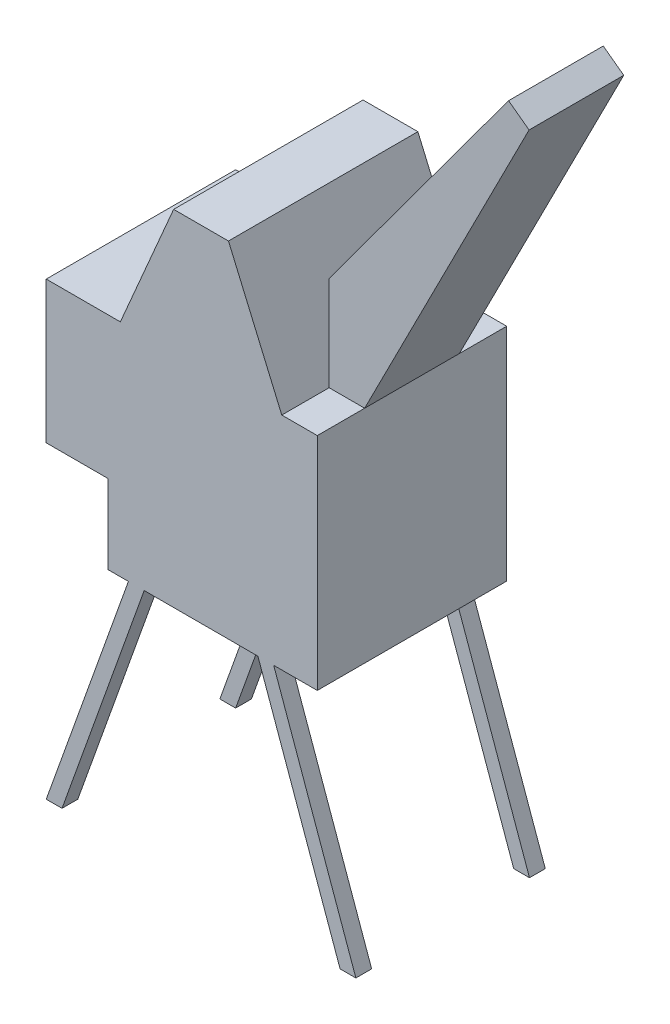
SolidWorks part; units mm, degrees
ref_plane "Front Plane" through (0, 0, 0) normal (0, 0, 1) x (1, 0, 0)
ref_plane "Top Plane" through (0, 0, 0) normal (0, 1, 0) x (1, 0, 0)
ref_plane "Right Plane" through (0, 0, 0) normal (1, 0, 0) x (0, 0, -1)
sketch "Sketch1" plane through (0, 0, 0) normal (0, 0, 1) x (1, 0, 0)
  line L0 (0, 0) -> (529.0109, 1478.7244)
  line L1 (529.0109, 1478.7244) -> (1993.215, 0)
  line L2 (1993.215, 0) -> (1464.2041, 1478.7244)
  line L3 (397.1811, 1478.7244) -> (1596.0339, 1478.7244)
  line L4 (1596.0339, 1478.7244) -> (1596.0339, 1986.7569)
  line L5 (1596.0339, 1986.7569) -> (397.1811, 1986.7569)
  line L6 (397.1811, 1986.7569) -> (397.1811, 1478.7244)
  line L7 (397.1811, 1986.7569) -> (0, 1986.7569)
  line L8 (0, 1986.7569) -> (0, 2899.7327)
  line L9 (0, 2899.7327) -> (1744.8315, 2899.7327)
  line L10 (1744.8315, 2899.7327) -> (1744.8315, 1986.7569)
  line L11 (1744.8315, 1986.7569) -> (1596.0339, 1986.7569)
  line L12 (727.2667, 2899.7327) -> (727.2667, 1986.7569)
  line L13 (1464.2041, 1478.7244) -> (0, 0)
  line L14 (1516.2315, 2899.7327) -> (1516.2315, 3509.3327)
  line L15 (1516.2315, 3509.3327) -> (2671.2271, 5077.4555)
  line L16 (2671.2271, 5077.4555) -> (2803.2371, 4980.224)
  line L17 (2803.2371, 4980.224) -> (1744.8315, 2899.7327)
  line L18 (476.9834, 2899.7327) -> (820.1619, 3698.5201)
  line L19 (820.1619, 3698.5201) -> (1173.0531, 3698.5201)
  line L20 (1173.0531, 3698.5201) -> (1516.2315, 2899.7327)
  line L21 (996.6075, 3698.5201) -> (996.6075, 1478.7244) construction
  line L22 (996.6075, 1478.7244) -> (996.6075, 0) construction
  point P25 (996.6075, 1006.4907)
  dimension "D1" = 228.6
  dimension "D2" = 609.6
  dimension "D3" = 2438.4
sketch "Sketch2" plane through (0, 0, 0) normal (0, 0, 1) x (1, 0, 0)
  line L0 (397.1811, 1478.7244) -> (1744.8315, 1478.7244)
  line L1 (1744.8315, 2899.7327) -> (1744.8315, 1478.7244)
  line L2 (0, 1986.7569) -> (397.1811, 1986.7569)
  line L3 (397.1811, 1986.7569) -> (397.1811, 1478.7244)
  line L4 (0, 1986.7569) -> (0, 2899.7327)
  line L6 (476.9834, 2899.7327) -> (820.1619, 3698.5201)
  line L7 (820.1619, 3698.5201) -> (1173.0531, 3698.5201)
  line L8 (1173.0531, 3698.5201) -> (1516.2315, 2899.7327)
  line L9 (1516.2315, 2899.7327) -> (1744.8315, 2899.7327)
  line L10 (0, 2899.7327) -> (476.9834, 2899.7327)
extrude "Boss-Extrude1" add sketch "Sketch2" along normal mid plane 1219.2
sketch "Sketch3" plane through (0, 0, 0) normal (0, 0, 1) x (1, 0, 0)
  line L0 (1516.2315, 3509.3327) -> (1516.2315, 2899.7327)
  line L1 (1516.2315, 2899.7327) -> (1744.8315, 2899.7327)
  line L2 (1744.8315, 2899.7327) -> (2803.2371, 4980.224)
  line L3 (2803.2371, 4980.224) -> (2671.2271, 5077.4555)
  line L4 (2671.2271, 5077.4555) -> (1516.2315, 3509.3327)
extrude "Boss-Extrude2" add sketch "Sketch3" along normal mid plane 609.6
sketch "Sketch4" plane through (0, 0, 609.6) normal (0, 0, 1) x (1, 0, 0)
  line L0 (529.0109, 1478.7244) -> (0, 0)
  line L1 (0, 0) -> (101.6, 0)
  line L2 (101.6, 0) -> (630.6109, 1478.7244)
  line L3 (397.1811, 1478.7244) -> (1596.0339, 1478.7244) construction
  line L4 (630.6109, 1478.7244) -> (529.0109, 1478.7244)
  line L5 (1464.2041, 1478.7244) -> (1362.6041, 1478.7244)
  line L6 (1362.6041, 1478.7244) -> (1891.615, 0)
  line L7 (1891.615, 0) -> (1993.215, 0)
  line L8 (1993.215, 0) -> (1464.2041, 1478.7244)
  dimension "D1" = 101.6
extrude "Boss-Extrude3" add sketch "Sketch4" against normal blind 101.6
mirror "Mirror1" about plane through (0, 0, 0) normal (0, 0, 1) of "Boss-Extrude3"
